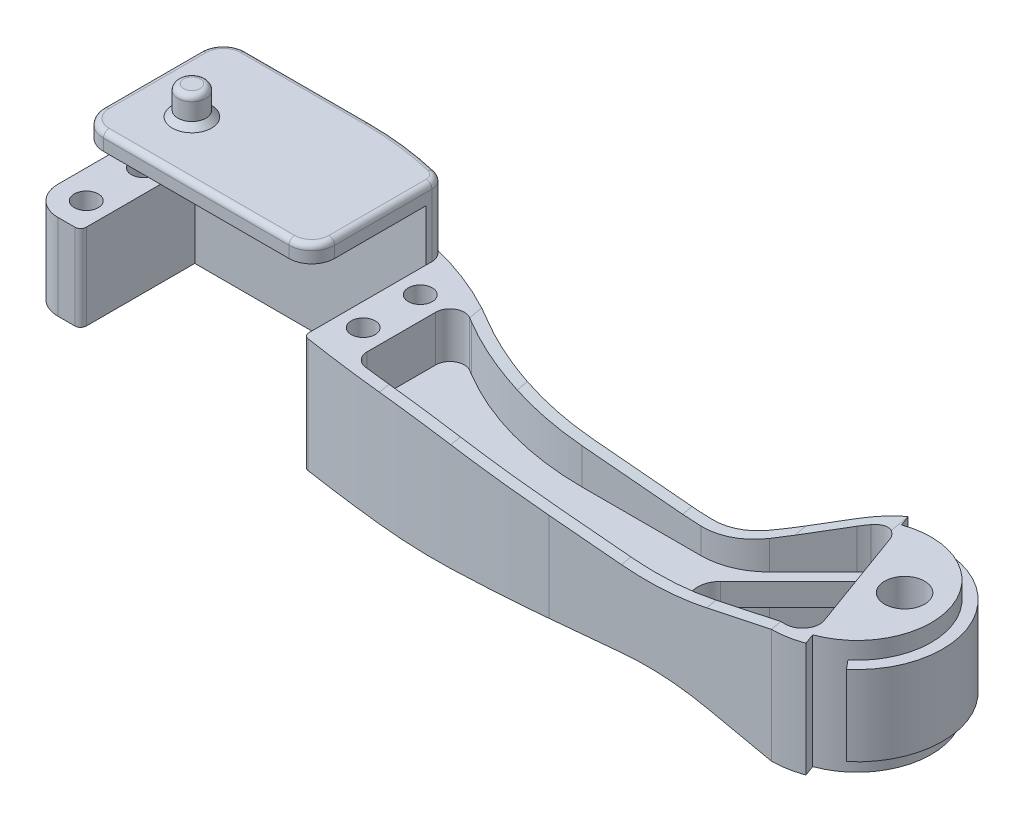
SolidWorks part; units mm, degrees
ref_plane "Alzado" through (0, 0, 0) normal (0, 0, 1) x (1, 0, 0)
ref_plane "Planta" through (0, 0, 0) normal (0, 1, 0) x (1, 0, 0)
ref_plane "Vista lateral" through (0, 0, 0) normal (1, 0, 0) x (0, 0, -1)
sketch "Croquis1" plane through (0, 0, 0) normal (0, 1, 0) x (1, 0, 0)
  line L0 (-65, 15) -> (-40.2965, 15)
  line L1 (-75, -15) -> (75, -15) construction
  line L2 (-75, -15) -> (-75, 15) construction
  line L3 (-75, 15) -> (75, 15) construction
  line L4 (75, -15) -> (75, 15) construction
  line L5 (-75, -15) -> (75, 15) construction
  line L6 (-75, 15) -> (75, -15) construction
  line L7 (13.7868, 0) -> (34.6447, 0)
  line L8 (41.7157, 2.9289) -> (49.3934, 10.6066)
  line L9 (60, -15) -> (21, -15)
  line L10 (-25.5, -10.5178) -> (-25.5, 10)
  line L11 (-25.5, 10) -> (-66, 10)
  line L12 (-66, 10) -> (-66, -9)
  line L13 (-67, -10) -> (-70, -10)
  line L14 (-75, -5) -> (-75, 5)
  line L18 (57.4617, 6.9739) -> (62.5383, -6.9739)
  line L19 (59.7192, -11) -> (43.109, -11)
  line L20 (40.2805, -4.1716) -> (52.5213, 8.0692)
  line L21 (60, 0) -> (60, 15) construction
  line L22 (57.4617, 6.9739) -> (54.8697, 14.0954) construction
  line L23 (62.5383, -6.9739) -> (65.1303, -14.0954) construction
  line L24 (60, 0) -> (69.6418, -11.4907) construction
  line L25 (54.8697, 14.0954) -> (55.5537, 12.216)
  line L26 (60, 15) -> (60, 13)
  line L27 (65.1303, -14.0954) -> (64.4463, -12.216)
  line L28 (69.6418, -11.4907) -> (68.3562, -9.9586)
  line L29 (60, 0) -> (66.108, 2.2231) construction
  arc A0 (-40.2965, 15) -> (-11.9671, 7.1429) centre (-40.2965, -40) cw
  arc A1 (-11.9671, 7.1429) -> (13.7868, 0) centre (13.7868, 50) ccw
  arc A3 (49.3934, 10.6066) -> (54.8697, 14.0954) centre (60, 0) cw
  arc A4 (21, -15) -> (-24.6522, -11.5061) centre (21, 285) cw
  arc A5 (-24.6522, -11.5061) -> (-25.5, -10.5178) centre (-24.5, -10.5178) cw
  arc A6 (-66, -9) -> (-67, -10) centre (-67, -9) cw
  arc A7 (-75, 5) -> (-65, 15) centre (-65, 5) cw
  arc A8 (-75, -5) -> (-70, -10) centre (-70, -5) ccw
  arc A9 (41.7157, 2.9289) -> (34.6447, 0) centre (34.6447, 10) cw
  arc A10 (43.109, -11) -> (40.2805, -4.1716) centre (43.109, -7) cw
  arc A11 (57.4617, 6.9739) -> (52.5213, 8.0692) centre (54.6426, 5.9479) ccw
  arc A12 (62.5383, -6.9739) -> (59.7192, -11) centre (59.7192, -8) cw
  arc A14 (65.1303, -14.0954) -> (60, -15) centre (60, 0) cw
  arc A15 (60, 15) -> (69.6418, -11.4907) centre (60, 0) cw
  arc A16 (64.4463, -12.216) -> (68.3562, -9.9586) centre (60, 0) ccw
  arc A17 (60, 13) -> (55.5537, 12.216) centre (60, 0) ccw
  circle A18 centre (66.108, 2.2231) radius 3.5
  point P0 (0, 0)
  point P33 (-75, -10)
  point P36 (60, 0)
  point P37 (60, 0)
  point P38 (60, 0)
  point P51 (38.7868, 0)
  dimension "D3" = 10
  dimension "D4" = 5
  dimension "D6" = 1
  dimension "D10" = 55
  dimension "D11" = 50
  dimension "D13" = 10
  dimension "D14" = 15
  dimension "D16" = 300
  dimension "D17" = 1
  dimension "D21" = 4
  dimension "D22" = 3
  dimension "D23" = 3
  dimension "D24" = 13
  dimension "D26" = 6.5
  dimension "D27" = 7
  dimension "D1" = 150
  dimension "D2" = 30
  dimension "D5" = 10
  dimension "D7" = 19
  dimension "D8" = 3
  dimension "D9" = 40.5
  dimension "D12" = 25
  dimension "D15" = 39
  dimension "D18" = 135
  dimension "D19" = 20
  dimension "D20" = 4
  dimension "D25" = 20
extrude "Saliente-Extruir1" add sketch "Croquis1" along normal mid plane 4
sketch "Croquis2" plane through (0, 0, 0) normal (0, 1, 0) x (1, 0, 0)
  line L0 (54.8697, 14.0954) -> (55.5537, 12.216) construction
  line L1 (41.7157, 2.9289) -> (49.3934, 10.6066) construction
  line L2 (13.7868, 0) -> (34.6447, 0) construction
  line L3 (60, -15) -> (21, -15) construction
  line L4 (-65, 15) -> (-40.2965, 15) construction
  line L5 (-25.5, -10.5178) -> (-25.5, 10) construction
  line L6 (-25.5, 10) -> (-66, 10) construction
  line L7 (-66, 10) -> (-66, -9) construction
  line L8 (-67, -10) -> (-70, -10) construction
  line L9 (-75, -5) -> (-75, 5) construction
  line L10 (54.8697, 14.0954) -> (55.5537, 12.216)
  line L11 (41.7157, 2.9289) -> (49.3934, 10.6066)
  line L12 (13.7868, 0) -> (34.6447, 0)
  line L13 (60, -15) -> (21, -15)
  line L14 (-65, 15) -> (-40.2965, 15)
  line L15 (-25.5, -10.5178) -> (-25.5, 10)
  line L16 (-25.5, 10) -> (-66, 10)
  line L17 (-66, 10) -> (-66, -9)
  line L18 (-67, -10) -> (-70, -10)
  line L19 (-75, -5) -> (-75, 5)
  line L20 (65.1303, -14.0954) -> (64.4463, -12.216) construction
  line L21 (65.1303, -14.0954) -> (64.4463, -12.216)
  line L22 (13.7868, -2) -> (34.6447, -2)
  line L23 (43.1299, 1.5147) -> (50.8076, 9.1924)
  line L24 (60, -13) -> (21, -13)
  line L25 (-17.5, 3.7074) -> (-17.5, -8.2989)
  line L26 (63.2627, -8.9641) -> (56.7373, 8.9641)
  arc A0 (-25.5, -10.5178) -> (-24.6522, -11.5061) centre (-24.5, -10.5178) ccw construction
  circle A1 centre (66.108, 2.2231) radius 3.5 construction
  arc A2 (54.8697, 14.0954) -> (49.3934, 10.6066) centre (60, 0) ccw construction
  arc A3 (34.6447, 0) -> (41.7157, 2.9289) centre (34.6447, 10) ccw construction
  arc A4 (60, -15) -> (65.1303, -14.0954) centre (60, 0) ccw construction
  arc A5 (-24.6522, -11.5061) -> (21, -15) centre (21, 285) ccw construction
  arc A6 (-11.9671, 7.1429) -> (13.7868, 0) centre (13.7868, 50) ccw construction
  arc A7 (-11.9671, 7.1429) -> (-40.2965, 15) centre (-40.2965, -40) ccw construction
  arc A8 (-67, -10) -> (-66, -9) centre (-67, -9) ccw construction
  arc A9 (-75, -5) -> (-70, -10) centre (-70, -5) ccw construction
  arc A10 (-65, 15) -> (-75, 5) centre (-65, 5) ccw construction
  arc A11 (-25.5, -10.5178) -> (-24.6522, -11.5061) centre (-24.5, -10.5178) ccw
  circle A12 centre (66.108, 2.2231) radius 3.5
  arc A13 (54.8697, 14.0954) -> (49.3934, 10.6066) centre (60, 0) ccw
  arc A14 (34.6447, 0) -> (41.7157, 2.9289) centre (34.6447, 10) ccw
  arc A15 (60, -15) -> (65.1303, -14.0954) centre (60, 0) ccw
  arc A16 (-24.6522, -11.5061) -> (21, -15) centre (21, 285) ccw
  arc A17 (-11.9671, 7.1429) -> (13.7868, 0) centre (13.7868, 50) ccw
  arc A18 (-11.9671, 7.1429) -> (-40.2965, 15) centre (-40.2965, -40) ccw
  arc A19 (-67, -10) -> (-66, -9) centre (-67, -9) ccw
  arc A20 (-75, -5) -> (-70, -10) centre (-70, -5) ccw
  arc A21 (-65, 15) -> (-75, 5) centre (-65, 5) ccw
  arc A22 (64.4463, -12.216) -> (55.5537, 12.216) centre (60, 0) ccw
  arc A23 (-12.9973, 5.4286) -> (-13.7477, 5.8712) centre (-40.2965, -40) ccw
  arc A24 (-12.9973, 5.4286) -> (13.7868, -2) centre (13.7868, 50) ccw
  arc A25 (34.6447, -2) -> (43.1299, 1.5147) centre (34.6447, 10) ccw
  arc A26 (52.0937, 10.3194) -> (50.8076, 9.1924) centre (60, 0) ccw
  arc A27 (-15.3046, -10.7803) -> (21, -13) centre (21, 285) ccw
  arc A28 (60, -13) -> (60.5767, -12.9872) centre (60, 0) ccw
  arc A29 (-12.9973, 5.4286) -> (-40.2965, 13) centre (-40.2965, -40) ccw construction
  arc A30 (-24.3478, -9.5294) -> (21, -13) centre (21, 285) ccw construction
  arc A31 (55.5537, 12.216) -> (50.8076, 9.1924) centre (60, 0) ccw construction
  arc A32 (56.7373, 8.9641) -> (52.0937, 10.3194) centre (53.9183, 7.938) ccw
  arc A33 (60, -13) -> (64.4463, -12.216) centre (60, 0) ccw construction
  arc A34 (63.2627, -8.9641) -> (60.5767, -12.9872) centre (60.4436, -9.9902) cw
  arc A35 (-13.7477, 5.8712) -> (-17.5, 3.7074) centre (-15, 3.7074) ccw
  arc A36 (-17.5, -8.2989) -> (-15.3046, -10.7803) centre (-15, -8.2989) ccw
  dimension "D1" = 2
  dimension "D4" = 3
  dimension "D5" = 3
  dimension "D6" = 2.5
  dimension "D7" = 2.5
  dimension "D3" = 8
  dimension "D2" = 2
extrude "Saliente-Extruir2" add sketch "Croquis2" along normal mid plane 20
sketch "Croquis3" plane through (0, 0, 0) normal (0, 1, 0) x (1, 0, 0)
  line L0 (69.6418, -11.4907) -> (68.3562, -9.9586) construction
  line L1 (60, 15) -> (60, 13) construction
  line L2 (69.6418, -11.4907) -> (68.3562, -9.9586)
  line L3 (60, 15) -> (60, 13)
  arc A0 (69.6418, -11.4907) -> (60, 15) centre (60, 0) ccw construction
  arc A1 (69.6418, -11.4907) -> (60, 15) centre (60, 0) ccw
  arc A2 (68.3562, -9.9586) -> (60, 13) centre (60, 0) ccw
extrude "Saliente-Extruir3" add sketch "Croquis3" along normal mid plane 14
sketch "Croquis4" plane through (0, 0, 15) normal (0, 0, 1) x (1, 0, 0)
  line L1 (60, 10) -> (60, -10) construction
  line L2 (60, 10) -> (-10, 10)
  line L3 (60, 10) -> (60, -10) construction
  line L4 (60, 10) -> (48.6517, 7.5772)
  line L5 (33.7402, 6.6757) -> (3.4163, 9.3988)
  line L6 (16.5, 0) -> (-16.5, 0) construction
  line L7 (60, -10) -> (-10, -10)
  line L8 (33.7402, -6.6757) -> (3.4163, -9.3988)
  line L9 (60, -10) -> (48.6517, -7.5772)
  arc A1 (3.4163, 9.3988) -> (-10, 10) centre (-10, -140) ccw
  arc A2 (48.6517, 7.5772) -> (33.7402, 6.6757) centre (38.2123, 56.4753) cw
  arc A3 (3.4163, -9.3988) -> (-10, -10) centre (-10, 140) cw
  arc A4 (48.6517, -7.5772) -> (33.7402, -6.6757) centre (38.2123, -56.4753) ccw
  point P12 (41.264, 6)
  dimension "D2" = 6
  dimension "D3" = 150
  dimension "D5" = 50
  dimension "D1" = 70
  dimension "D4" = 38
sketch "Croquis5" plane through (0, 0, 0) normal (0, 1, 0) x (1, 0, 0)
  line L0 (60, -15) -> (54.8697, 14.0954) construction
  arc A0 (60, -15) -> (65.1303, -14.0954) centre (60, 0) ccw construction
  arc A1 (54.8697, 14.0954) -> (49.3934, 10.6066) centre (60, 0) ccw construction
  arc A2 (60, -15) -> (65.1303, -14.0954) centre (60, 0) ccw
  arc A3 (54.8697, 14.0954) -> (49.3934, 10.6066) centre (60, 0) ccw
extrude "Cortar-Extruir1" cut sketch "Croquis4" along direction (-0.1736, 0, -0.9848) on the side against the normal through all
sketch "Croquis7" plane through (0, 10, 0) normal (0, 1, 0) x (1, 0, 0)
  line L0 (-70, -10) -> (-67, -10) construction
  line L1 (-75, 5) -> (-75, -5) construction
  line L2 (-70, -10) -> (-67, -10)
  line L3 (-75, 5) -> (-75, -5)
  line L6 (-65, 15) -> (-62, 15)
  line L7 (-66, -9) -> (-66, 11)
  arc A0 (-67, -10) -> (-66, -9) centre (-67, -9) ccw construction
  arc A1 (-75, -5) -> (-70, -10) centre (-70, -5) ccw construction
  arc A3 (-67, -10) -> (-66, -9) centre (-67, -9) ccw
  arc A4 (-75, -5) -> (-70, -10) centre (-70, -5) ccw
  arc A6 (-65, 15) -> (-75, 5) centre (-65, 5) ccw construction
  arc A7 (-65, 15) -> (-75, 5) centre (-65, 5) ccw
  arc A8 (-62, 15) -> (-66, 11) centre (-62, 11) ccw
  dimension "D1" = 4
extrude "Cortar-Extruir3" cut sketch "Croquis7" against normal blind 5
sketch "Croquis8" plane through (0, 10, 0) normal (0, 1, 0) x (1, 0, 0)
  line L7 (-40.2965, 15) -> (-62, 15) construction
  line L8 (-66, 10) -> (-66, 11) construction
  line L11 (-66, 10) -> (-25.5, 10) construction
  line L12 (-40.2965, 15) -> (-62, 15)
  line L13 (-66, 10) -> (-66, 11)
  line L14 (-66, 10) -> (-25.5, 10)
  line L15 (-25.5, 10) -> (-25.5, 11.0397)
  arc A6 (-14.1211, 8.372) -> (-40.2965, 15) centre (-40.2965, -40) ccw construction
  arc A7 (-62, 15) -> (-66, 11) centre (-62, 11) ccw construction
  arc A8 (-27.4145, 13.4701) -> (-40.2965, 15) centre (-40.2965, -40) ccw
  arc A9 (-62, 15) -> (-66, 11) centre (-62, 11) ccw
  arc A10 (-25.5, 11.0397) -> (-27.4145, 13.4701) centre (-28, 11.0397) ccw
  dimension "D1" = 2.5
extrude "Saliente-Extruir4" add sketch "Croquis8" along normal blind 9
sketch "Croquis9" plane through (0, 19, 0) normal (0, 1, 0) x (1, 0, 0)
  line L0 (-40.2965, 15) -> (-62, 15) construction
  line L1 (-40.2965, 15) -> (-62, 15)
  line L2 (-66, 11) -> (-66, -6)
  line L3 (-62, -10) -> (-29.5, -10)
  line L4 (-25.5, -6) -> (-25.5, 11.0397)
  line L5 (-70, -10) -> (-67, -10) construction
  line L6 (-70, -10) -> (-67, -10) construction
  arc A0 (-25.5, 11.0397) -> (-27.4145, 13.4701) centre (-28, 11.0397) ccw construction
  arc A1 (-27.4145, 13.4701) -> (-40.2965, 15) centre (-40.2965, -40) ccw construction
  arc A2 (-62, 15) -> (-66, 11) centre (-62, 11) ccw construction
  arc A3 (-25.5, 11.0397) -> (-27.4145, 13.4701) centre (-28, 11.0397) ccw
  arc A4 (-27.4145, 13.4701) -> (-40.2965, 15) centre (-40.2965, -40) ccw
  arc A5 (-62, 15) -> (-66, 11) centre (-62, 11) ccw
  arc A6 (-25.5, -6) -> (-29.5, -10) centre (-29.5, -6) cw
  arc A7 (-62, -10) -> (-66, -6) centre (-62, -6) cw
  dimension "D1" = 4
extrude "Saliente-Extruir5" add sketch "Croquis9" along normal blind 3
sketch "Croquis10" plane through (0, -10, 0) normal (0, -1, 0) x (1, 0, 0)
  line L0 (-45.75, -10) -> (-45.75, -15) construction
  line L1 (-66, -10) -> (-25.5, -10) construction
  line L2 (-40.2965, -15) -> (-65, -15) construction
  circle A1 centre (-70, -5) radius 2.1
  circle A2 centre (-70, 5) radius 2.1
  circle A3 centre (-21.5, -5) radius 2.1
  circle A4 centre (-21.5, 5) radius 2.1
  dimension "D1" = 10
  dimension "D3" = 4.2
  dimension "D2" = 10
  dimension "D4" = 4
extrude "Cortar-Extruir4" cut sketch "Croquis10" against normal through all
sketch "Croquis11" plane through (0, 22, 0) normal (0, 1, 0) x (1, 0, 0)
  line L0 (-66, 11) -> (-66, -6) construction
  line L1 (-62, -10) -> (-29.5, -10) construction
  circle A0 centre (-56.5, 0) radius 2.45
  dimension "D1" = 9.5
  dimension "D2" = 4.9
  dimension "D3" = 10
extrude "Saliente-Extruir6" add sketch "Croquis11" along normal blind 5
fillet "Redondeo1" radius 1 1 edges at (-56.5, 27, 2.45)
chamfer "Chaflán1" distance 1 angle 45 1 edges at (-56.5, 22, 2.45)
fillet "Redondeo2" radius 1 9 edges at (-64.8284, 22, 8.8284) (-66, 22, -2.5) (-64.8284, 22, -13.8284) (-51.1482, 22, -15) (-33.8102, 22, -14.6162) (-26.0361, 22, -12.5866) (-25.5, 22, -2.5198) (-26.6716, 22, 8.8284) (-45.75, 22, 10)
